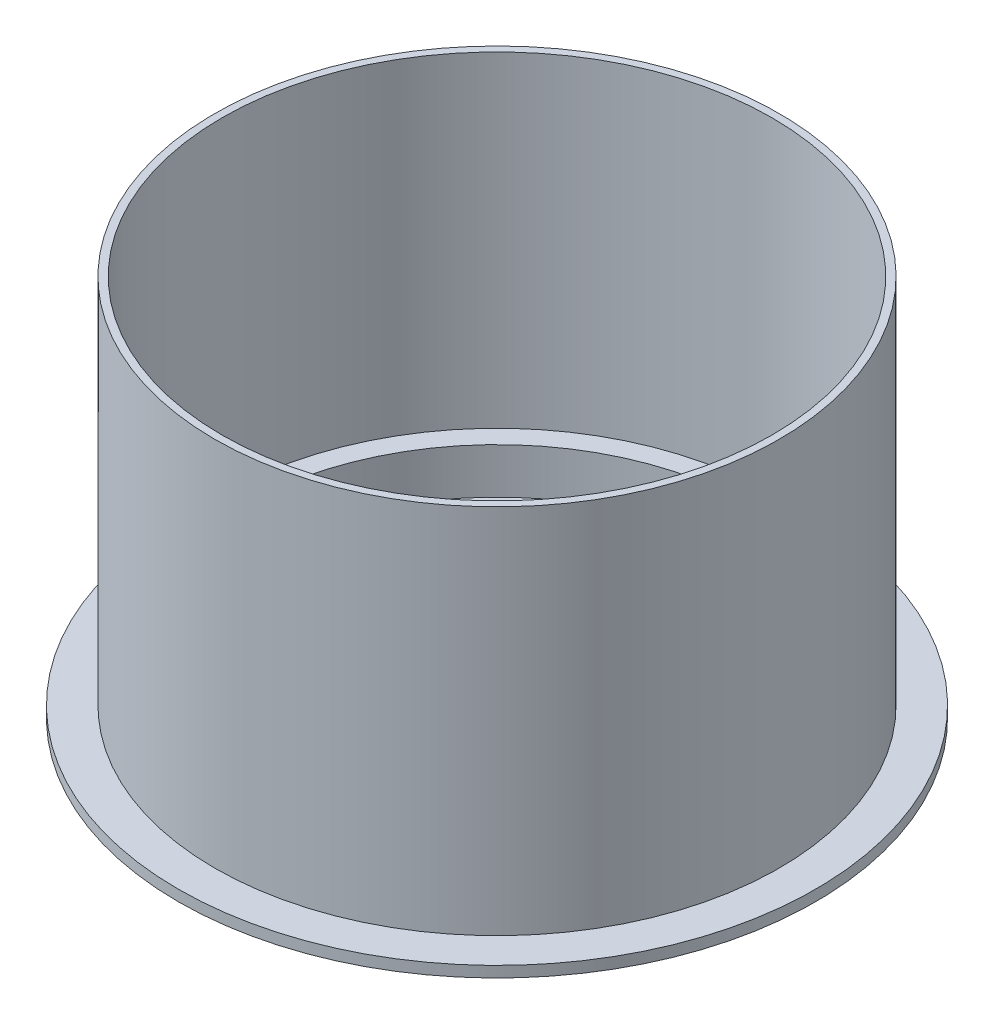
SolidWorks part; units mm, degrees
ref_plane "Front Plane" through (0, 0, 0) normal (0, 0, 1) x (1, 0, 0)
ref_plane "Top Plane" through (0, 0, 0) normal (0, 1, 0) x (1, 0, 0)
ref_plane "Right Plane" through (0, 0, 0) normal (1, 0, 0) x (0, 0, -1)
sketch "Floor Sketch" plane through (0, 0, 0) normal (0, 1, 0) x (1, 0, 0)
  circle A0 centre (0, 0) radius 175
  circle A1 centre (0, 0) radius 12.5
  dimension "D1" = 350
  dimension "D2" = 25
extrude "Floor - Tank Lid" add sketch "Floor Sketch" along normal blind 6
sketch "Basket Ledge Sketch" plane through (0, 0, 0) normal (0, 1, 0) x (1, 0, 0)
  circle A0 centre (0, 0) radius 152
  circle A1 centre (0, 0) radius 140
  dimension "D1" = 304
  dimension "D2" = 280
extrude "Basket Ledge" add sketch "Basket Ledge Sketch" along normal blind 31
sketch "Housing Wall Sketch" plane through (0, 0, 0) normal (0, 1, 0) x (1, 0, 0)
  circle A0 centre (0, 0) radius 155
  circle A1 centre (0, 0) radius 151
  dimension "D1" = 310
  dimension "D2" = 302
extrude "Housing Wall" add sketch "Housing Wall Sketch" along normal blind 210
